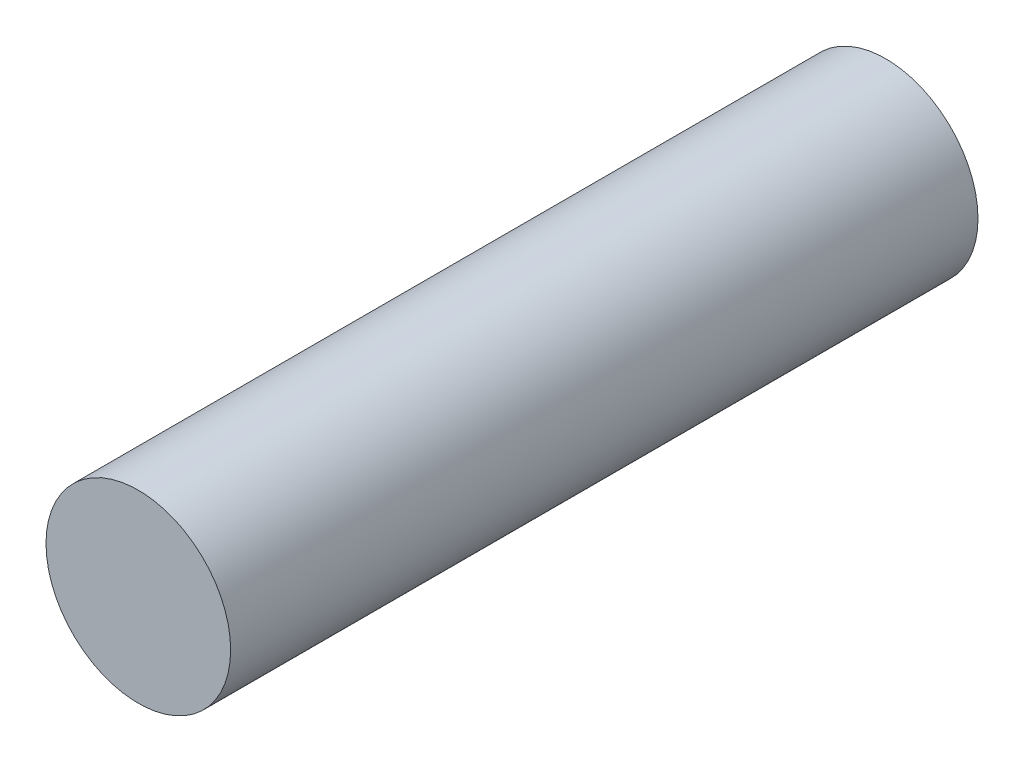
SolidWorks part; units mm, degrees
ref_plane "Alzado" through (0, 0, 0) normal (0, 0, 1) x (1, 0, 0)
ref_plane "Planta" through (0, 0, 0) normal (0, 1, 0) x (1, 0, 0)
ref_plane "Vista lateral" through (0, 0, 0) normal (1, 0, 0) x (0, 0, -1)
sketch "Croquis1" plane through (0, 0, 0) normal (0, 0, 1) x (1, 0, 0)
  circle A0 centre (0, 0) radius 5
  dimension "D1" = 10
extrude "Saliente-Extruir1" add sketch "Croquis1" along normal blind 40.475
